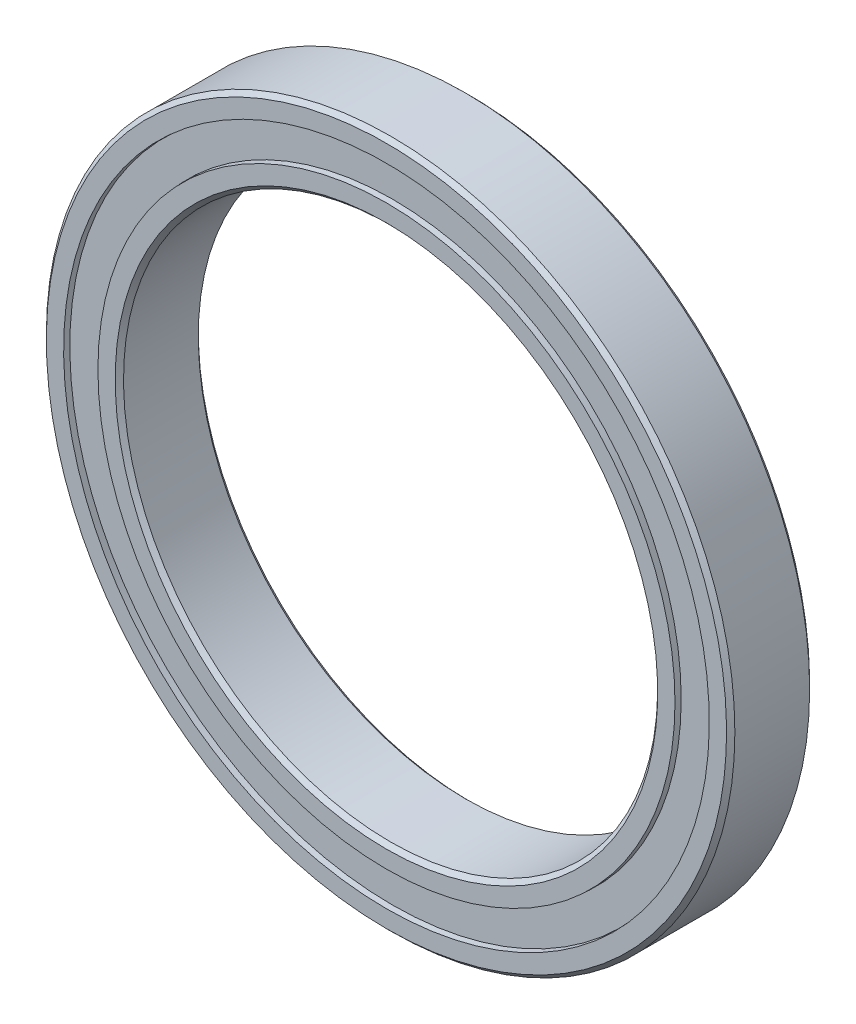
SolidWorks part; units mm, degrees
ref_plane "Front Plane" through (0, 0, 0) normal (0, 0, 1) x (1, 0, 0)
ref_plane "Top Plane" through (0, 0, 0) normal (0, 1, 0) x (1, 0, 0)
ref_plane "Right Plane" through (0, 0, 0) normal (1, 0, 0) x (0, 0, -1)
sketch "Sketch1" plane through (0, 0, 0) normal (0, 0, 1) x (1, 0, 0)
  circle A0 centre (0, 0) radius 29
  circle A1 centre (0, 0) radius 22.5
  dimension "OD" = 58
  dimension "ID" = 45
  dimension "For Shaft Diameter" = 45
  dimension "For Housing ID" = 58
sketch "Sketch8" plane through (0, 0, 0) normal (1, 0, 0) x (0, 0, -1)
  line L1 (-3.5, 29) -> (3.5, 29)
  line L2 (-3.5, 29) -> (-3.5, -29)
  line L3 (-3.5, -29) -> (3.5, -29)
  line L4 (3.5, 29) -> (3.5, -29)
  line L5 (-3.5, 29) -> (3.5, -29) construction
  line L6 (-3.5, -29) -> (3.5, 29) construction
  point P0 (0, 0)
  point P6 (0, -29)
  dimension "Width" = 7
sketch "Sketch5" plane through (0, 0, 0) normal (1, 0, 0) x (0, 0, -1)
  line L0 (-3.5, 0) -> (3.5, 0) construction
  line L1 (0, 29) -> (0, -29) construction
  line L2 (3.15, 29) -> (-3.15, 29)
  line L3 (-3.15, 29) -> (-3.5, 28.65)
  line L4 (-3.5, 28.65) -> (-3.5, 27.1944)
  line L5 (-3.5, 27.1944) -> (-1.5556, 27.1944)
  line L6 (3.5, 27.1944) -> (1.5556, 27.1944)
  line L7 (3.5, 28.65) -> (3.5, 27.1944)
  line L8 (3.15, 29) -> (3.5, 28.65)
  line L9 (0, 29) -> (0, 25.75) construction
  line L10 (0, 25.75) -> (0, 22.5) construction
  line L11 (-2.1228, 25.75) -> (-3.5, 25.75) construction
  line L12 (2.6209, 24.331) -> (3.0019, 24.331)
  line L13 (-2.6209, 24.331) -> (-3.0019, 24.331)
  line L14 (-2.6209, 24.331) -> (-2.6209, 27.169)
  line L15 (-2.6209, 27.169) -> (-3.0019, 27.169)
  line L16 (-3.0019, 24.331) -> (-3.0019, 27.169)
  line L17 (-2.6209, 24.331) -> (-3.0019, 27.169) construction
  line L18 (-2.6209, 27.169) -> (-3.0019, 24.331) construction
  line L19 (3.0019, 24.331) -> (3.0019, 27.169)
  line L20 (2.6209, 27.169) -> (3.0019, 27.169)
  line L21 (2.6209, 24.331) -> (2.6209, 27.169)
  line L22 (0, 29) -> (0, -29) construction
  line L23 (3.5, 0) -> (3.5, 29) construction
  line L24 (3.5, 29) -> (3.15, 29) construction
  line L25 (-3.5, 0) -> (-3.5, 29) construction
  line L26 (-3.5, 29) -> (-3.15, 29) construction
  line L27 (3.5, 0) -> (3.5, -29) construction
  line L28 (-3.5, 0) -> (-3.5, -29) construction
  line L29 (-3.5, -29) -> (3.5, -29) construction
  arc A0 (-1.5556, 27.1944) -> (1.5556, 27.1944) centre (0, 25.75) cw
  circle A1 centre (0, 25.75) radius 2.1228 construction
  point P14 (0, 22.5)
  point P15 (-2.8114, 25.75)
  dimension "D1" = 45
  dimension "D2" = 0.35
  dimension "D3" = 3.1111
  dimension "D4" = 1.4444
  dimension "D5" = 0.381
  dimension "D6" = 0.0254
revolve "Revolve1" add sketch "Sketch5" angle 360 about L0
sketch "Sketch3" plane through (0, 0, 0) normal (1, 0, 0) x (0, 0, -1)
  line L0 (-3.5, 24.3056) -> (-1.5556, 24.3056)
  line L1 (0, 29) -> (0, -29) construction
  line L2 (-3.5, 28.65) -> (-3.5, 27.1944) construction
  line L3 (-3.5, 24.3056) -> (-3.5, 22.85)
  line L4 (-3.15, 29) -> (-3.5, 28.65) construction
  line L5 (-3.5, 22.85) -> (-3.15, 22.5)
  line L6 (-3.15, 22.5) -> (3.15, 22.5)
  line L7 (3.15, 29) -> (3.15, -29) construction
  line L8 (3.15, 22.5) -> (3.5, 22.85)
  line L9 (3.5, -28.65) -> (3.5, 28.65) construction
  line L10 (3.5, 22.85) -> (3.5, 24.3056)
  line L11 (3.5, 24.3056) -> (1.5556, 24.3056)
  line L13 (3.15, 29) -> (3.5, 28.65) construction
  arc A0 (1.5556, 27.1944) -> (-1.5556, 27.1944) centre (0, 25.75) ccw construction
  arc A1 (1.5556, 24.3056) -> (-1.5556, 24.3056) centre (0, 25.75) cw
revolve "Revolve3" add sketch "Sketch3" angle 360 about L0
sketch "Sketch4" plane through (0, 0, 0) normal (1, 0, 0) x (0, 0, -1)
  line L0 (-2.1228, 25.75) -> (2.1228, 25.75)
  arc A2 (-2.1228, 25.75) -> (2.1228, 25.75) centre (0, 25.75) cw
  arc A3 (1.5556, 27.1944) -> (-1.5556, 27.1944) centre (0, 25.75) ccw construction
revolve "Revolve4" add sketch "Sketch4" angle 360 about L0
pattern_circular "CirPattern1" count 21 every 17.143 about axis through (0, 0, 0) along (0, 0, 1) of bodies 104
equation "\"D2@Sketch5\" = \"Width@Sketch8\" * .05"
equation "\"D3@Sketch5\" = \"Width@Sketch8\" / 2.25"
equation "\"D4@Sketch5\"=((\"OD@Sketch1\"-\"ID@Sketch1\")/2)/4.5"
equation "\"D2@CirPattern1\" = 360/\"Balls@CirPattern1\""
